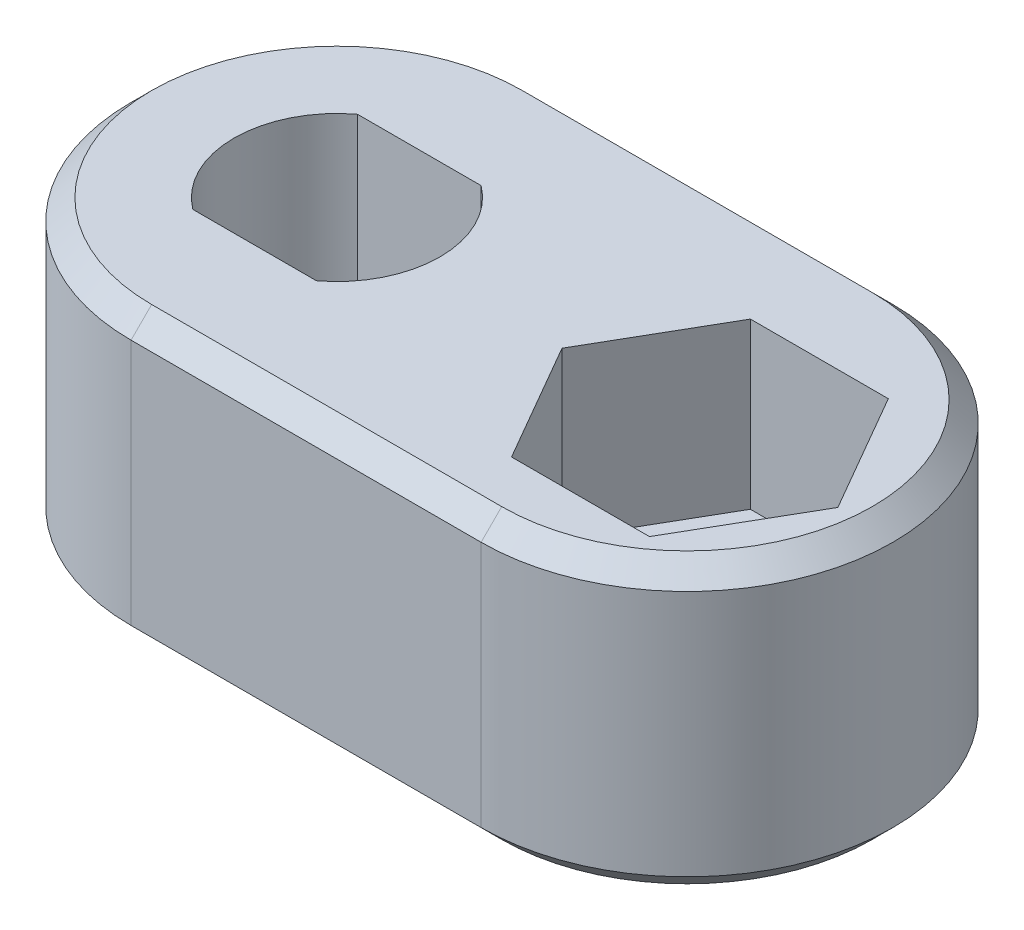
SolidWorks part; units mm, degrees
material "POM 乙缩醛共聚物"
ref_plane "前视基准面" through (0, 0, 0) normal (0, 0, 1) x (1, 0, 0)
ref_plane "上视基准面" through (0, 0, 0) normal (0, 1, 0) x (1, 0, 0)
ref_plane "右视基准面" through (0, 0, 0) normal (1, 0, 0) x (0, 0, -1)
sketch "草图1" plane through (0, 0, 0) normal (0, 1, 0) x (1, 0, 0)
  line L0 (-4.25, 0) -> (4.25, 0) construction
  line L1 (-4.25, 5) -> (4.25, 5)
  line L2 (-4.25, -5) -> (4.25, -5)
  arc A0 (-4.25, 5) -> (-4.25, -5) centre (-4.25, 0) ccw
  arc A1 (4.25, -5) -> (4.25, 5) centre (4.25, 0) ccw
  point P2 (0, 0)
  dimension "D1" = 10
  dimension "D2" = 8.5
extrude "凸台-拉伸1" add sketch "草图1" along normal blind 7
sketch "草图2" plane through (0, 7, 0) normal (0, 1, 0) x (1, 0, 0)
  line L0 (0, 0) -> (-9.1692, 0) construction
  line L1 (-5.75, 2) -> (-2.75, 2)
  line L2 (-5.75, -2) -> (-2.75, -2)
  circle A0 centre (-4.25, 0) radius 2.5
  point P8 (-4.25, 0)
  dimension "D2" = 5
  dimension "D1" = 4
extrude "切除-拉伸1" cut sketch "草图2" against normal blind 4
hole_wizard "M3 六角凹锥坑螺钉的锥形沉头孔1" positions "草图8" profile "草图9" countersink size "M3" standard "ISO"
sketch "草图8" plane through (0, 0, 0) normal (0, -1, 0) x (-1, 0, 0)
  point P0 (4.25, 0)
sketch "草图9" plane through (-4.25, 0, 0) normal (1, 0, 0) x (0, 0, -1)
  line L0 (0, 0) -> (0, 8.5215)
  line L1 (0, 8.5215) -> (1.7, 7.5)
  line L2 (1.7, 7.5) -> (1.7, 1.66)
  line L3 (1.7, 1.66) -> (3.36, 0)
  line L5 (3.36, 0) -> (0, 0)
  line L6 (-1.7, 1.66) -> (-3.36, 0) construction
  line L10 (0, 8.5215) -> (-1.7, 7.5) construction
  line L11 (0, -6.35) -> (0, 107.95) construction
  dimension "孔直径" = 3.4
  dimension "孔深度" = 7.5
  dimension "近端锥形沉头孔直径" = 6.72
  dimension "近端锥形沉头孔角度" = 90
  dimension "导头角度" = 118
hole_wizard "孔1" positions "草图10" profile "草图11" legacy end condition through all
sketch "草图10" plane through (0, 7, 0) normal (0, 1, 0) x (1, 0, 0)
  point P0 (5, -0.4368)
sketch "草图11" plane through (5, 7, 0.4368) normal (1, 0, 0) x (0, 0, 1)
  line L0 (0, 0) -> (0, 7)
  line L1 (0, 7) -> (2.075, 7)
  line L2 (2.075, 7) -> (2.075, 0)
  line L3 (2.075, 0) -> (0, 0)
  line L4 (0, 110) -> (0, -10) construction
  dimension "直径" = 4.15
  dimension "深度" = 7
sketch "草图12" plane through (0, 7, 0) normal (0, 1, 0) x (1, 0, 0)
  line L0 (4.25, 5) -> (-4.25, 5) construction
  line L1 (8.3486, -0.4368) -> (6.6743, 2.4632)
  line L2 (6.6743, 2.4632) -> (3.3257, 2.4632)
  line L3 (3.3257, 2.4632) -> (1.6514, -0.4368)
  line L4 (1.6514, -0.4368) -> (3.3257, -3.3368)
  line L5 (3.3257, -3.3368) -> (6.6743, -3.3368)
  line L6 (6.6743, -3.3368) -> (8.3486, -0.4368)
  circle A0 centre (5, -0.4368) radius 2.9 construction
  dimension "D1" = 5.8
extrude "切除-拉伸2" cut sketch "草图12" against normal blind 4
chamfer "倒角1" distance 0.5 angle 45 8 edges at (0, 0, 5) (9.25, 0, 0) (-9.25, 0, 0) (0, 0, -5) (0, 7, 5) (9.25, 7, 0) (-9.25, 7, 0) (0, 7, -5)
